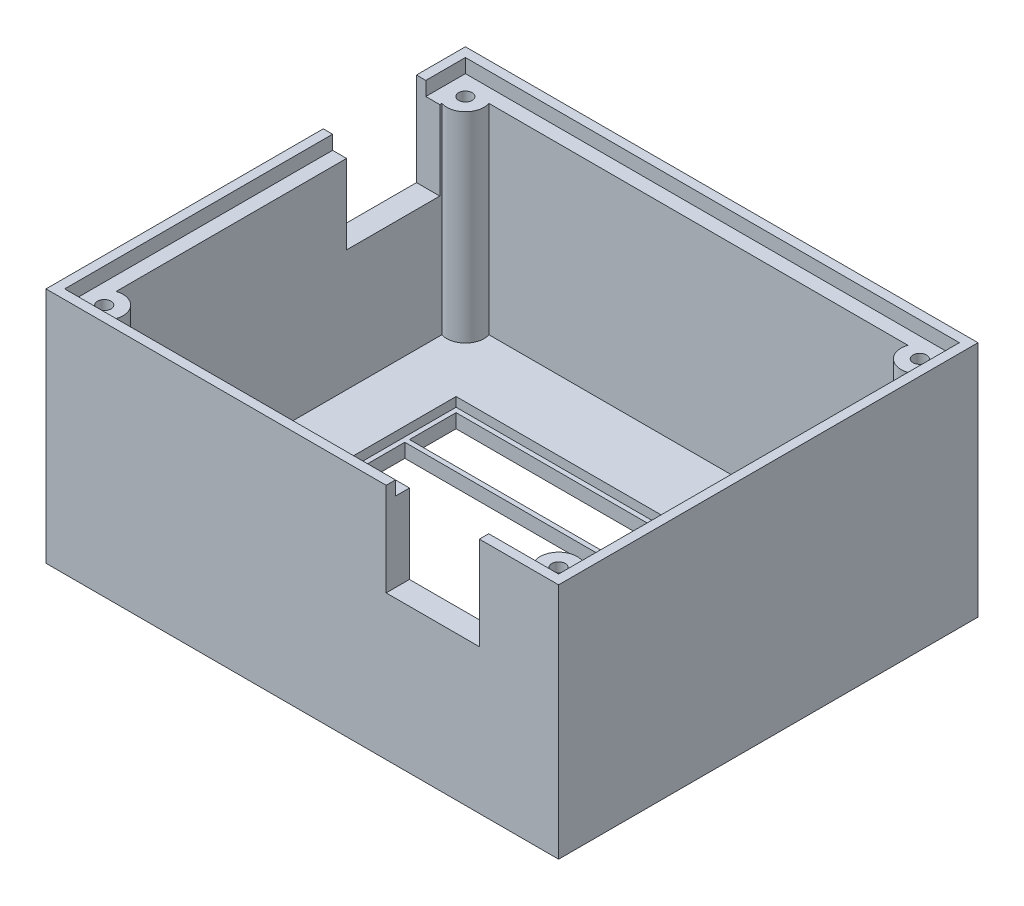
SolidWorks part; units mm, degrees
ref_plane "Front Plane" through (0, 0, 0) normal (0, 0, 1) x (1, 0, 0)
ref_plane "Top Plane" through (0, 0, 0) normal (0, 1, 0) x (1, 0, 0)
ref_plane "Right Plane" through (0, 0, 0) normal (1, 0, 0) x (0, 0, -1)
sketch "Sketch1" plane through (0, 0, 0) normal (0, 1, 0) x (1, 0, 0)
  line L1 (-55, -45) -> (55, -45)
  line L2 (-55, -45) -> (-55, 45)
  line L3 (-55, 45) -> (55, 45)
  line L4 (55, -45) -> (55, 45)
extrude "Boss-Extrude1" add sketch "Sketch1" along normal blind 51
sketch "Sketch2" plane through (0, 51, 0) normal (0, 1, 0) x (1, 0, 0)
  line L1 (-50, 40) -> (50, 40)
  line L2 (-50, 40) -> (-50, -40)
  line L3 (-50, -40) -> (50, -40)
  line L4 (50, 40) -> (50, -40)
extrude "Cut-Extrude1" cut sketch "Sketch2" against normal blind 46
sketch "Sketch3" plane through (0, 51, 0) normal (0, 1, 0) x (1, 0, 0)
  line L1 (-53, 43) -> (53, 43)
  line L2 (-53, 43) -> (-53, 40)
  line L3 (-53, 40) -> (53, 40)
  line L4 (53, 43) -> (53, 40)
extrude "Cut-Extrude2" cut sketch "Sketch3" against normal blind 3
sketch "Sketch5" plane through (0, 51, 0) normal (0, 1, 0) x (1, 0, 0)
  line L1 (53, 40) -> (50, 40)
  line L2 (53, 40) -> (53, -43)
  line L3 (53, -43) -> (50, -43)
  line L4 (50, 40) -> (50, -43)
extrude "Cut-Extrude3" cut sketch "Sketch5" against normal blind 3
sketch "Sketch6" plane through (0, 51, 0) normal (0, 1, 0) x (1, 0, 0)
  line L1 (50, -43) -> (-53, -43)
  line L2 (50, -43) -> (50, -40)
  line L3 (50, -40) -> (-53, -40)
  line L4 (-53, -43) -> (-53, -40)
extrude "Cut-Extrude4" cut sketch "Sketch6" against normal blind 3
sketch "Sketch7" plane through (0, 51, 0) normal (0, 1, 0) x (1, 0, 0)
  line L1 (-53, 40) -> (-50, 40)
  line L2 (-53, 40) -> (-53, -40)
  line L3 (-53, -40) -> (-50, -40)
  line L4 (-50, 40) -> (-50, -40)
extrude "Cut-Extrude5" cut sketch "Sketch7" against normal blind 3
sketch "Sketch9" plane through (0, 5, 0) normal (0, 1, 0) x (1, 0, 0)
  circle A0 centre (-48.75, 38.75) radius 4
extrude "Boss-Extrude2" add sketch "Sketch9" along normal blind 43 contours A0
sketch "Sketch10" plane through (0, 5, 0) normal (0, 1, 0) x (1, 0, 0)
  circle A0 centre (48.75, 38.75) radius 4
  circle A1 centre (48.75, -38.75) radius 4
  circle A2 centre (-48.75, -38.75) radius 4
extrude "Boss-Extrude3" add sketch "Sketch10" along normal blind 43
hole_wizard "M2.5 Clearance Hole1" positions "Sketch11" profile "Sketch12" hole size "M2.5" standard "ANSI Metric"
sketch "Sketch11" plane through (0, 48, 0) normal (0, 1, 0) x (1, 0, 0)
  point P0 (-48.75, 38.75)
  point P3 (48.75, 38.75)
  point P6 (48.75, -38.75)
  point P9 (-48.75, -38.75)
sketch "Sketch12" plane through (-48.75, 48, -38.75) normal (1, 0, 0) x (0, 0, 1)
  line L0 (0, 0) -> (0, 5.8712)
  line L1 (0, 5.8712) -> (1.45, 5)
  line L2 (1.45, 5) -> (1.45, 0)
  line L5 (1.45, 0) -> (0, 0)
  line L10 (0, 5.8712) -> (-1.45, 5) construction
  line L11 (0, -6.35) -> (0, 107.95) construction
  dimension "Hole Dia." = 2.9
  dimension "Hole Depth" = 5
  dimension "Drill Angle" = 118
sketch "Sketch14" plane through (-55, 0, 0) normal (-1, 0, 0) x (0, 0, 1)
  line L1 (-34.5, 51) -> (-14.5, 51)
  line L2 (-34.5, 51) -> (-34.5, 31)
  line L3 (-34.5, 31) -> (-14.5, 31)
  line L4 (-14.5, 51) -> (-14.5, 31)
extrude "Cut-Extrude6" cut sketch "Sketch14" against normal blind 5
sketch "Sketch15" plane through (0, 0, 45) normal (0, 0, 1) x (1, 0, 0)
  line L1 (38, 51) -> (18, 51)
  line L2 (38, 51) -> (38, 31)
  line L3 (38, 31) -> (18, 31)
  line L4 (18, 51) -> (18, 31)
extrude "Cut-Extrude7" cut sketch "Sketch15" against normal blind 5
sketch "Sketch16" plane through (0, 5, 0) normal (0, 1, 0) x (1, 0, 0)
  line L1 (36, 13) -> (-36, 13)
  line L2 (36, 13) -> (36, -13)
  line L3 (36, -13) -> (-36, -13)
  line L4 (-36, 13) -> (-36, -13)
extrude "Cut-Extrude8" cut sketch "Sketch16" against normal blind 5
sketch "Sketch17" plane through (0, 0, 0) normal (0, -1, 0) x (1, 0, 0)
  line L1 (-36, -14) -> (36, -14)
  line L2 (-36, -14) -> (-36, -24)
  line L3 (-36, -24) -> (36, -24)
  line L4 (36, -14) -> (36, -24)
extrude "Cut-Extrude9" cut sketch "Sketch17" against normal blind 5
hole_wizard "M6 Clearance Hole2" positions "Sketch20" profile "Sketch21" hole size "M6" standard "ANSI Metric" end condition through all
sketch "Sketch20" plane through (0, 0, 0) normal (0, -1, 0) x (-1, 0, 0)
  point P0 (40, -28)
  point P8 (0, 0)
  point P9 (38.9655, -26.8062)
sketch "Sketch21" plane through (-40, 0, 28) normal (1, 0, 0) x (0, 0, -1)
  line L0 (0, 0) -> (0, 51)
  line L1 (0, 51) -> (3.3, 51)
  line L2 (3.3, 51) -> (3.3, 0)
  line L5 (3.3, 0) -> (0, 0)
  line L11 (0, -6.35) -> (0, 107.95) construction
  dimension "Thru Hole Dia." = 6.6
  dimension "Thru Hole Depth" = 51
sketch "Sketch22" plane through (0, 5, 0) normal (0, 1, 0) x (1, 0, 0)
  line L1 (-37, 25) -> (37, 25)
  line L2 (-37, 25) -> (-37, -14)
  line L3 (-37, -14) -> (37, -14)
  line L4 (37, 25) -> (37, -14)
extrude "Cut-Extrude10" cut sketch "Sketch22" against normal blind 2
